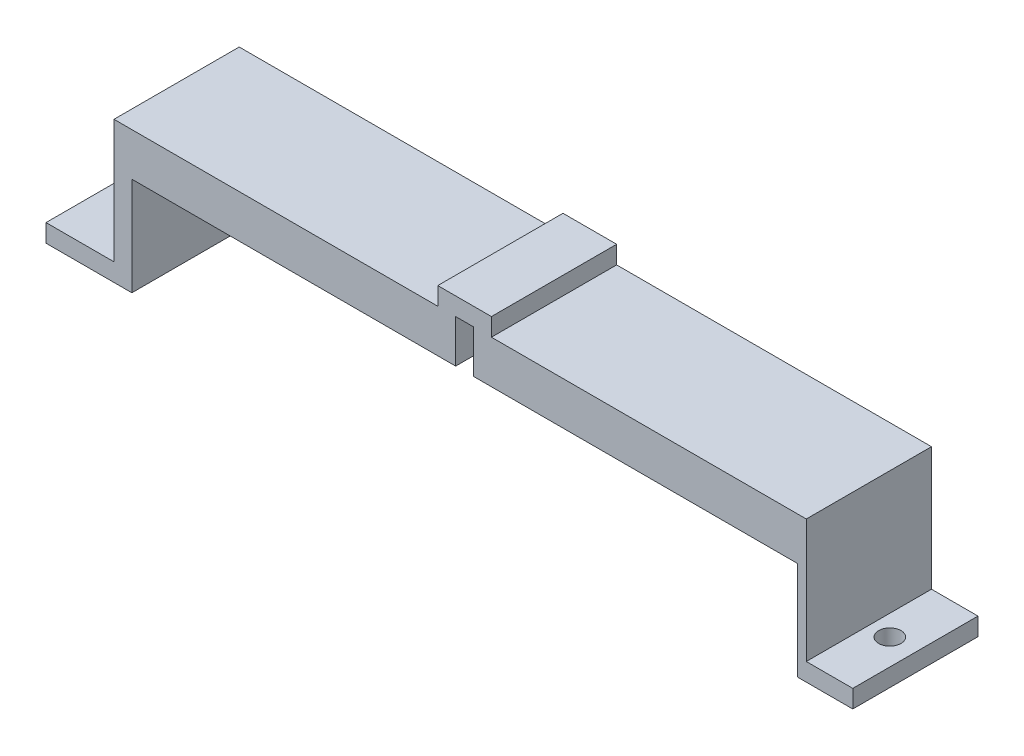
SolidWorks part; units mm, degrees
ref_plane "Front Plane" through (0, 0, 0) normal (0, 0, 1) x (1, 0, 0)
ref_plane "Top Plane" through (0, 0, 0) normal (0, 1, 0) x (1, 0, 0)
ref_plane "Right Plane" through (0, 0, 0) normal (1, 0, 0) x (0, 0, -1)
sketch "Sketch3" plane through (0, 0, 0) normal (0, 0, 1) x (1, 0, 0)
  line L0 (2.54, -2.54) -> (5.08, -2.54)
  line L1 (5.08, -2.54) -> (5.08, -8.636)
  line L3 (51.054, -22.606) -> (58.928, -22.606)
  line L5 (7.62, -2.54) -> (7.62, 0)
  line L6 (7.62, 0) -> (0, 0)
  line L7 (0, 0) -> (0, -2.54)
  line L11 (2.54, -8.636) -> (2.54, -2.54)
  line L18 (51.054, -22.606) -> (51.054, -8.636)
  line L21 (-43.434, -8.636) -> (-43.434, -22.606)
  line L23 (-55.626, -20.066) -> (-45.974, -20.066)
  line L24 (-45.974, -20.066) -> (-45.974, -2.54)
  line L27 (58.928, -22.606) -> (58.928, -20.066)
  line L28 (58.928, -20.066) -> (52.324, -20.066)
  line L29 (52.324, -20.066) -> (52.324, -2.54)
  line L31 (7.62, -2.54) -> (52.324, -2.54)
  line L32 (5.08, -8.636) -> (51.054, -8.636)
  line L33 (-45.974, -2.54) -> (0, -2.54)
  line L34 (-43.434, -8.636) -> (2.54, -8.636)
  line L35 (-55.626, -20.066) -> (-55.626, -22.606)
  line L36 (-55.626, -22.606) -> (-43.434, -22.606)
  dimension "D1" = 2.54
  dimension "D2" = 2.54
  dimension "D3" = 2.54
  dimension "D4" = 2.54
  dimension "D5" = 1.27
  dimension "D6" = 45.974
  dimension "D7" = 45.974
  dimension "D8" = 2.54
  dimension "D9" = 2.54
  dimension "D10" = 2.54
  dimension "D11" = 13.97
  dimension "D12" = 2.54
  dimension "D13" = 6.096
  dimension "D14" = 7.874
  dimension "D15" = 12.192
  dimension "D16" = 6.096
extrude "Boss-Extrude1" add sketch "Sketch3" along normal blind 17.78
sketch "Sketch4" plane through (0, -22.606, 0) normal (0, -1, 0) x (1, 0, 0)
  circle A0 centre (-51.943, 8.8399) radius 1.5875
  circle A1 centre (55.245, 8.8399) radius 1.5875
extrude "Cut-Extrude1" cut sketch "Sketch4" against normal through all
